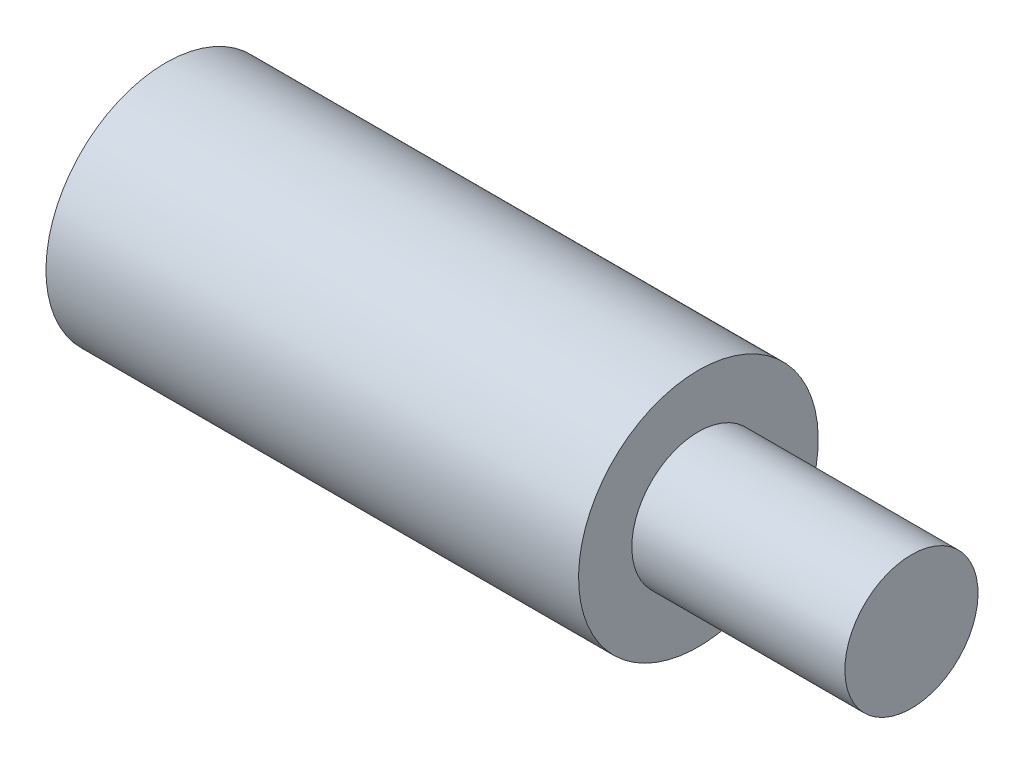
SolidWorks part; units mm, degrees
material "6061 合金"
ref_plane "前视基准面" through (0, 0, 0) normal (0, 0, 1) x (1, 0, 0)
ref_plane "上视基准面" through (0, 0, 0) normal (0, 1, 0) x (1, 0, 0)
ref_plane "右视基准面" through (0, 0, 0) normal (1, 0, 0) x (0, 0, -1)
sketch "草图2" plane through (0, 0, 0) normal (0, 0, 1) x (1, 0, 0)
  line L0 (0, 0) -> (0, 9)
  line L1 (0, 9) -> (40, 9)
  line L5 (56, 0) -> (0, 0)
  line L6 (40, 9) -> (40, 5)
  line L7 (40, 5) -> (56, 5)
  line L8 (56, 5) -> (56, 0)
  dimension "D1" = 9
  dimension "D2" = 56
  dimension "D3" = 40
  dimension "D4" = 5
revolve "旋转1" add sketch "草图2" angle 360 about L5
sketch "草图3" plane through (0, 0, 0) normal (-1, 0, 0) x (0, 0, 1)
  line L1 (-5, 5) -> (5, 5) construction
  line L2 (-5, 5) -> (-5, -5) construction
  line L3 (-5, -5) -> (5, -5) construction
  line L4 (5, 5) -> (5, -5) construction
  line L5 (0, -5) -> (0, 5) construction
  line L6 (-5, 0) -> (5, 0) construction
  circle A0 centre (5, 5) radius 1.2
  circle A1 centre (-5, 5) radius 1.2
  circle A2 centre (-5, -5) radius 1.2
  circle A3 centre (5, -5) radius 1.2
  point P112 (0, 0)
  dimension "D2" = 2.4
  dimension "D1" = 10
hole_wizard "M3 螺纹孔1" positions "草图4" profile "草图5" tap size "M3" standard "GB"
sketch "草图4" plane through (0, 0, 0) normal (-1, 0, 0) x (0, 0, 1)
  point P0 (-5, 5)
  point P3 (5, 5)
  point P6 (5, -5)
  point P9 (-5, -5)
sketch "草图5" plane through (0, 5, -5) normal (0, 1, 0) x (0, 0, 1)
  line L0 (0, 0) -> (0, 5.7511)
  line L1 (0, 5.7511) -> (1.25, 5)
  line L2 (1.25, 5) -> (1.25, 0)
  line L5 (1.25, 0) -> (0, 0)
  line L10 (0, 5.7511) -> (-1.25, 5) construction
  line L11 (0, -6.35) -> (0, 107.95) construction
  dimension "螺纹孔钻头直径" = 2.5
  dimension "螺纹孔钻头深度" = 5
  dimension "导头角度" = 118
cosmetic thread "孔螺蚊线1" parameters "D1"=5, "D2"=3
cosmetic thread "孔螺蚊线2" parameters "D1"=5, "D2"=3
cosmetic thread "孔螺蚊线3" parameters "D1"=5, "D2"=3
cosmetic thread "孔螺蚊线4" parameters "D1"=5, "D2"=3
